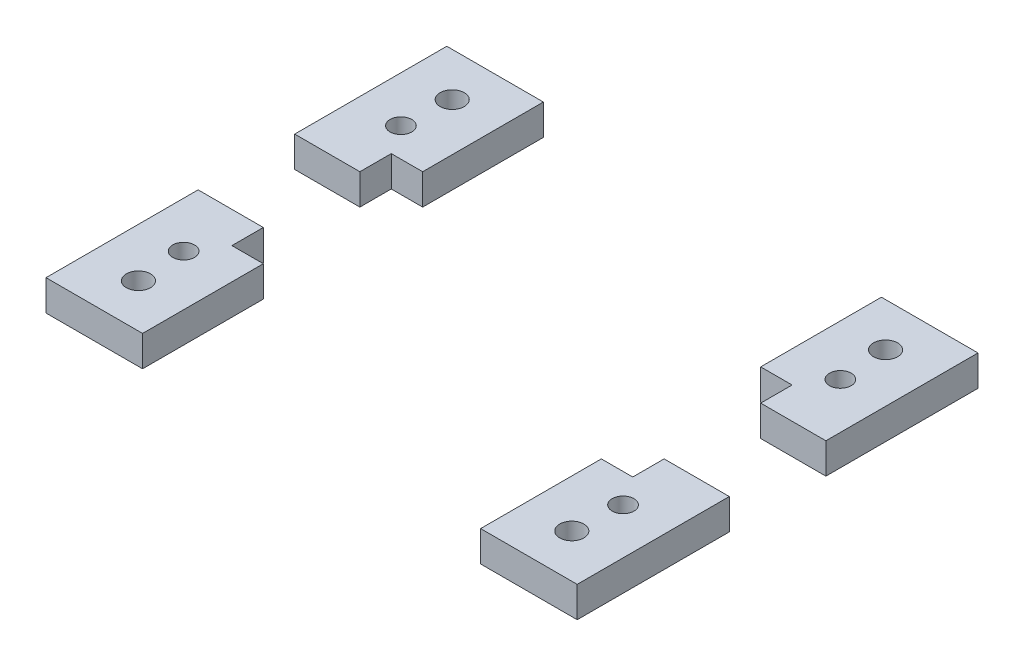
SolidWorks part; units mm, degrees
ref_plane "Front Plane" through (0, 0, 0) normal (0, 0, 1) x (1, 0, 0)
ref_plane "Top Plane" through (0, 0, 0) normal (0, 1, 0) x (1, 0, 0)
ref_plane "Right Plane" through (0, 0, 0) normal (1, 0, 0) x (0, 0, -1)
sketch "Sketch1" plane through (0, 0, 0) normal (0, 1, 0) x (1, 0, 0)
  line L1 (-41.5, 16.5) -> (41.5, 16.5)
  line L2 (-41.5, 16.5) -> (-41.5, -16.5)
  line L3 (-41.5, -16.5) -> (41.5, -16.5)
  line L4 (41.5, 16.5) -> (41.5, -16.5)
  line L5 (-41.5, 16.5) -> (41.5, -16.5) construction
  line L6 (-41.5, -16.5) -> (41.5, 16.5) construction
  point P0 (0, 0)
  dimension "D2" = 83
  dimension "D1" = 33
extrude "Extrude-Thin1" add sketch "Sketch1" along normal blind 3.175 and the other way blind 3.175 thin thin type one direction wall 25
sketch "Sketch2" plane through (0, 0, 0) normal (0, 1, 0) x (1, 0, 0)
  line L0 (-66.5, -41.5) -> (66.5, -41.5) construction
  line L1 (-75, 10) -> (-66.5, 10)
  line L2 (-75, 10) -> (-75, -10)
  line L3 (-75, -10) -> (-66.5, -10)
  line L4 (75, 10) -> (75, -10)
  line L5 (-75, 10) -> (75, -10) construction
  line L6 (-75, -10) -> (75, 10) construction
  line L7 (-35, -50) -> (35, -50)
  line L8 (-35, -50) -> (-35, 50)
  line L9 (-35, 50) -> (35, 50)
  line L10 (35, -50) -> (35, 50)
  line L11 (-35, -50) -> (35, 50) construction
  line L12 (-35, 50) -> (35, -50) construction
  line L13 (66.5, -41.5) -> (55, -41.5)
  line L14 (66.5, -41.5) -> (66.5, -10)
  line L16 (55, -41.5) -> (55, -10)
  line L17 (66.5, -41.5) -> (66.5, 41.5) construction
  line L18 (0, -55) -> (0, 55) construction
  line L19 (-66.5, -41.5) -> (-66.5, -10)
  line L20 (-66.5, -41.5) -> (-55, -41.5)
  line L21 (-55, -41.5) -> (-55, -10)
  line L22 (-55, 0) -> (55, 0) construction
  line L23 (-55, 41.5) -> (-55, 10)
  line L24 (-66.5, 41.5) -> (-55, 41.5)
  line L25 (-66.5, 41.5) -> (-66.5, 10)
  line L26 (66.5, 41.5) -> (66.5, 10)
  line L27 (66.5, 41.5) -> (55, 41.5)
  line L28 (55, 41.5) -> (55, 10)
  line L29 (66.5, -10) -> (75, -10)
  line L30 (66.5, 10) -> (75, 10)
  line L31 (-55, -10) -> (55, -10)
  line L32 (-55, 10) -> (55, 10)
  point P0 (0, 0)
  point P6 (0, 0)
  dimension "D1" = 100
  dimension "D2" = 70
  dimension "D3" = 150
  dimension "D4" = 20
  dimension "D5" = 11.5
extrude "Cut-Extrude3" cut sketch "Sketch2" along normal through all both and the other way through all contours L1 L10 L9 L8 | L10 L3 L4 L1 | L7 L10 L3 L8 | L3 L8 L1 L2
sketch "Sketch3" plane through (0, 0, 0) normal (0, 1, 0) x (1, 0, 0)
  line L0 (0, -1.7463) -> (0, 1.7463) construction
  line L1 (-45.5, -22.5) -> (45.5, -22.5) construction
  line L2 (-45.5, -22.5) -> (-45.5, 22.5) construction
  line L3 (-45.5, 22.5) -> (45.5, 22.5) construction
  line L4 (45.5, -22.5) -> (45.5, 22.5) construction
  line L5 (-45.5, -22.5) -> (45.5, 22.5) construction
  line L6 (-45.5, 22.5) -> (45.5, -22.5) construction
  line L7 (-1.7463, 0) -> (1.7463, 0) construction
  line L9 (44.8716, -32.4881) -> (-44.8716, -32.4881) construction
  line L10 (44.8716, -32.4881) -> (44.8716, 32.4881) construction
  line L11 (44.8716, 32.4881) -> (-44.8716, 32.4881) construction
  line L12 (-44.8716, -32.4881) -> (-44.8716, 32.4881) construction
  line L13 (44.8716, -32.4881) -> (-44.8716, 32.4881) construction
  line L14 (44.8716, 32.4881) -> (-44.8716, -32.4881) construction
  circle A0 centre (-45.5, 22.5) radius 2.25
  circle A1 centre (45.5, 22.5) radius 2.25
  circle A2 centre (45.5, -22.5) radius 2.25
  circle A3 centre (-45.5, -22.5) radius 2.25
  circle A4 centre (-44.8716, 32.4881) radius 2.5
  circle A5 centre (-44.8716, -32.4881) radius 2.5
  circle A6 centre (44.8716, -32.4881) radius 2.5
  circle A7 centre (44.8716, 32.4881) radius 2.5
  point P0 (0, 0)
  point P16 (0, 0)
  dimension "D3" = 4.5
  dimension "D4" = 5
  dimension "D1" = 91
  dimension "D2" = 45
  dimension "D5" = 64.9762
  dimension "D6" = 89.7432
extrude "Cut-Extrude4" cut sketch "Sketch3" along normal through all both and the other way through all
